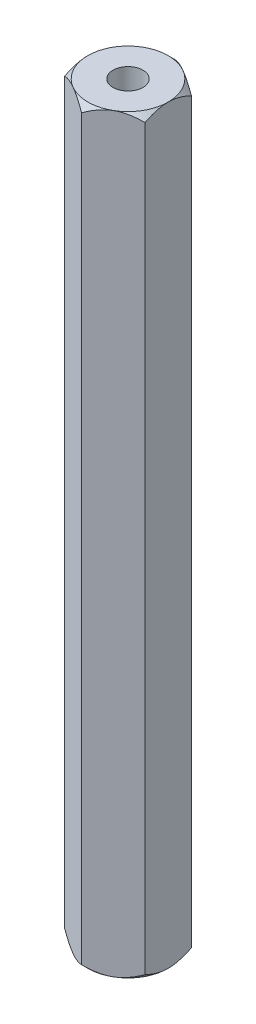
SolidWorks part; units mm, degrees
ref_plane "Front Plane" through (0, 0, 0) normal (0, 0, 1) x (1, 0, 0)
ref_plane "Top Plane" through (0, 0, 0) normal (0, 1, 0) x (1, 0, 0)
ref_plane "Right Plane" through (0, 0, 0) normal (1, 0, 0) x (0, 0, -1)
sketch "Sketch1" plane through (0, 0, 0) normal (0, 0, 1) x (1, 0, 0)
  line L0 (0, -22.225) -> (0, 39.0763) construction
  line L2 (0, -22.225) -> (2.3813, -22.225)
  line L3 (0, -22.225) -> (0, 22.225)
  line L4 (0, 22.225) -> (2.3813, 22.225)
  line L5 (3.175, -21.4313) -> (3.175, 21.4313)
  line L7 (2.3813, 22.225) -> (3.175, 21.4313)
  line L8 (2.3813, -22.225) -> (3.175, -21.4313)
  point P13 (0, 0)
  dimension "D1" = 6.35
  dimension "D2" = 44.45
  dimension "D5" = 4.7625
revolve "Revolve1" add sketch "Sketch1" angle 360 about L0
sketch "Sketch5" plane through (0, 22.225, 0) normal (0, 1, 0) x (1, 0, 0)
  line L1 (2.3813, -1.3748) -> (2.3812, 1.3748)
  line L2 (2.3812, 1.3748) -> (0, 2.7496)
  line L3 (0, 2.7496) -> (-2.3813, 1.3748)
  line L4 (-2.3813, 1.3748) -> (-2.3813, -1.3748)
  line L5 (-2.3813, -1.3748) -> (0, -2.7496)
  line L6 (0, -2.7496) -> (2.3813, -1.3748)
  circle A0 centre (0, 0) radius 2.3813 construction
  circle A1 centre (0, 0) radius 3.175 construction
  circle A2 centre (0, 0) radius 3.175
  dimension "D1" = 4.7625
extrude "Cut-Extrude1" cut sketch "Sketch5" against normal through all
hole_wizard "#2-56 Tapped Hole1" positions "Sketch6" profile "Sketch7" tap size "#2-56" standard "ANSI Inch" end condition through all
sketch "Sketch6" plane through (0, -22.225, 0) normal (0, -1, 0) x (-1, 0, 0)
  point P0 (0, 0)
cosmetic thread "Hole Thread1" parameters "D2"=2.1844
sketch "Sketch7" plane through (0, -22.225, 0) normal (1, 0, 0) x (0, 0, -1)
  line L0 (0, 0) -> (0, 44.45)
  line L1 (0, 44.45) -> (0.889, 44.45)
  line L2 (0.889, 44.45) -> (0.889, 0)
  line L5 (0.889, 0) -> (0, 0)
  line L11 (0, -6.35) -> (0, 107.95) construction
  dimension "Thru Tap Drill Dia." = 1.778
  dimension "Thru Tap Drill Depth" = 44.45
